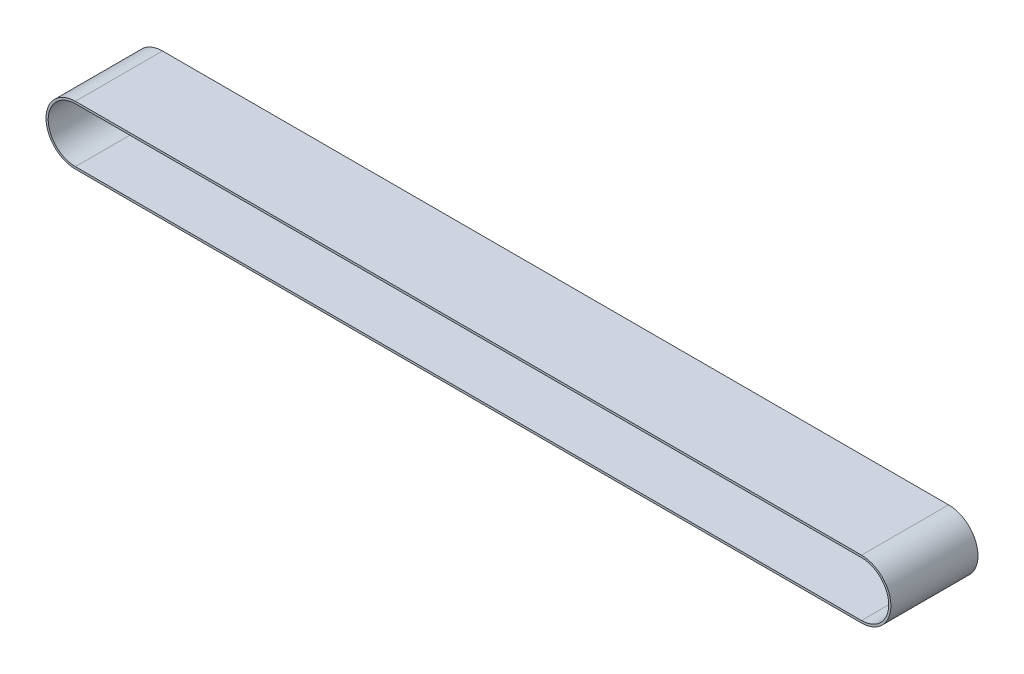
SolidWorks part; units mm, degrees
ref_plane "Plano frontal" through (0, 0, 0) normal (0, 0, 1) x (1, 0, 0)
ref_plane "Plano superior" through (0, 0, 0) normal (0, 1, 0) x (1, 0, 0)
ref_plane "Plano direito" through (0, 0, 0) normal (1, 0, 0) x (0, 0, -1)
sketch "Esboço1" plane through (0, 0, 0) normal (0, 0, 1) x (1, 0, 0)
  line L0 (-376.8772, 26.8463) -> (345.1228, 26.8463) construction
  line L1 (345.1228, 26.8463) -> (-376.8772, 26.8463) construction
  line L2 (345.1228, 1.8463) -> (-376.8772, 1.8463)
  line L3 (345.1228, 51.8463) -> (-376.8772, 51.8463)
  line L4 (345.1228, -0.1537) -> (-376.8772, -0.1537)
  line L5 (345.1228, 53.8463) -> (-376.8772, 53.8463)
  arc A0 (345.1228, 1.8463) -> (345.1228, 51.8463) centre (345.1228, 26.8463) ccw
  arc A1 (-376.8772, 51.8463) -> (-376.8772, 1.8463) centre (-376.8772, 26.8463) ccw
  arc A2 (-376.8772, 53.8463) -> (-376.8772, -0.1537) centre (-376.8772, 26.8463) ccw
  arc A3 (345.1228, -0.1537) -> (345.1228, 53.8463) centre (345.1228, 26.8463) ccw
  arc A4 (-376.8772, 53.8463) -> (-376.8772, -0.1537) centre (-376.8772, 26.8463) ccw construction
  point P0 (-15.8772, 26.8463)
  point P3 (0, 0)
  point P12 (0, 0)
  point P13 (0, 0)
  point P14 (0, 0)
  point P17 (-360.9905, 26.8463)
  point P19 (-377.5298, 26.8463)
  point P24 (-325.3211, 52.286)
  dimension "D2" = 25
  dimension "D1" = 722
  dimension "D3" = 2
extrude "Ressalto-extrusão1" add sketch "Esboço1" along normal blind 80
